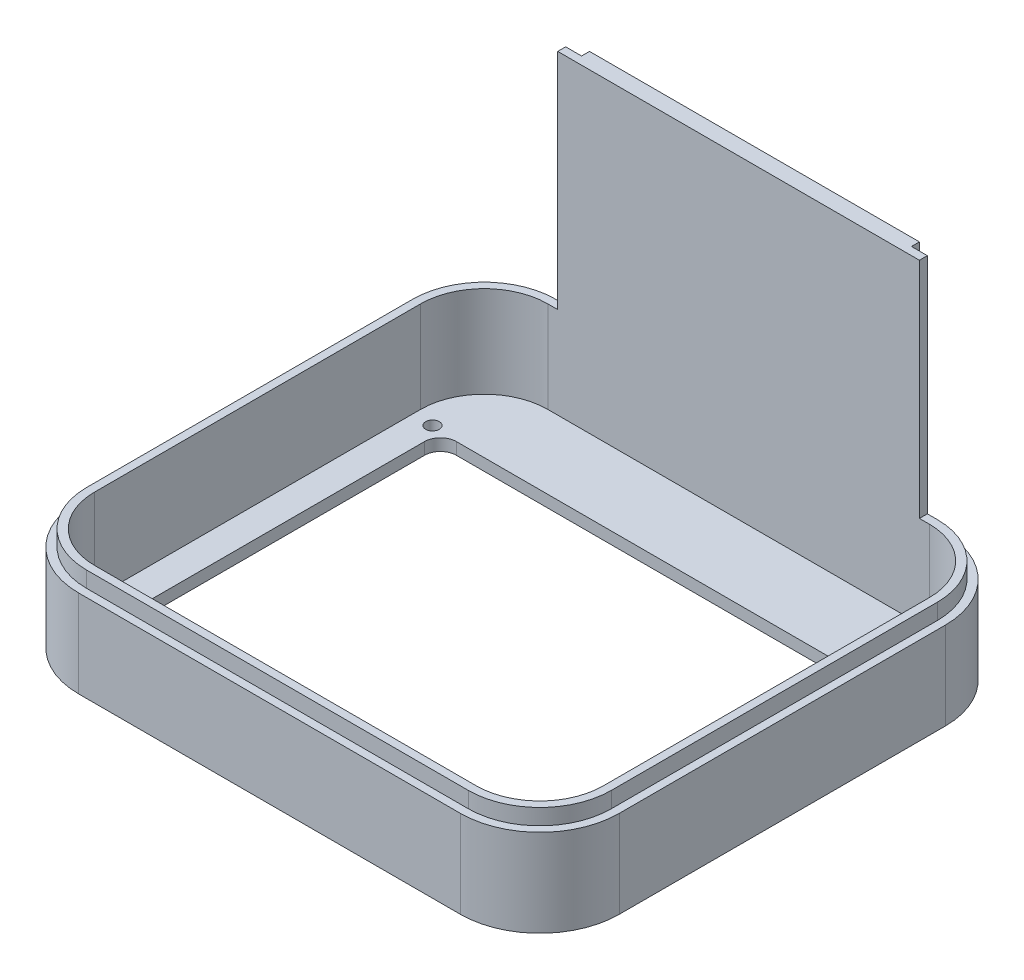
SolidWorks part; units mm, degrees
material "ABS"
ref_plane "Front Plane" through (0, 0, 0) normal (0, 0, 1) x (1, 0, 0)
ref_plane "Top Plane" through (0, 0, 0) normal (0, 1, 0) x (1, 0, 0)
ref_plane "Right Plane" through (0, 0, 0) normal (1, 0, 0) x (0, 0, -1)
sketch "Sketch1" plane through (0, 0, 0) normal (0, 1, 0) x (1, 0, 0)
  line L1 (-68, 61) -> (68, 61)
  line L2 (-68, 61) -> (-68, -61)
  line L3 (-68, -61) -> (68, -61)
  line L4 (68, 61) -> (68, -61)
  line L5 (-68, 61) -> (68, -61) construction
  line L6 (-68, -61) -> (68, 61) construction
  point P0 (0, 0)
  dimension "D1" = 136
  dimension "D2" = 122
extrude "Boss-Extrude1" add sketch "Sketch1" along normal blind 26
fillet "Fillet1" radius 20 4 edges at (-68, 13, 61) (68, 13, 61) (68, 13, -61) (-68, 13, -61)
shell "Shell1" thickness 4
sketch "Sketch2" plane through (0, 3, 0) normal (0, 1, 0) x (1, 0, 0)
  line L1 (-56.5, 38.5) -> (56.5, 38.5)
  line L2 (-56.5, 38.5) -> (-56.5, -38.5)
  line L3 (-56.5, -38.5) -> (56.5, -38.5)
  line L4 (56.5, 38.5) -> (56.5, -38.5)
  line L5 (-56.5, 38.5) -> (56.5, -38.5) construction
  line L6 (-56.5, -38.5) -> (56.5, 38.5) construction
  point P0 (0, 0)
  dimension "D1" = 113
  dimension "D2" = 77
extrude "Cut-Extrude1" cut sketch "Sketch2" against normal up to next
fillet "Fillet2" radius 4 4 edges at (-56.5, 1.5, 38.5) (56.5, 1.5, 38.5) (56.5, 1.5, -38.5) (-56.5, 1.5, -38.5)
hole_wizard "M3 Clearance Hole1" positions "Sketch3" profile "Sketch4" hole size "M3" standard "ANSI Metric" end condition through all
sketch "Sketch3" plane through (0, 3, 0) normal (0, 1, 0) x (1, 0, 0)
  line L0 (0, -14.3) -> (0, 14.3) construction
  line L1 (-14.3, 0) -> (14.3, 0) construction
  line L3 (0, 62.7849) -> (0, -61.8165) construction
  line L5 (-69.9424, 0) -> (69.1851, 0) construction
  point P0 (-59, 39)
  point P17 (59, 39)
  point P20 (59, -39)
  point P21 (-59, -39)
  dimension "D1" = 59
  dimension "D2" = 39
sketch "Sketch4" plane through (-59, 3, -39) normal (1, 0, 0) x (0, 0, 1)
  line L0 (0, 0) -> (0, 3)
  line L1 (0, 3) -> (1.7, 3)
  line L2 (1.7, 3) -> (1.7, 0)
  line L5 (1.7, 0) -> (0, 0)
  line L11 (0, -6.35) -> (0, 107.95) construction
  dimension "Thru Hole Dia." = 3.4
  dimension "Thru Hole Depth" = 3
sketch "Sketch5" plane through (0, 26, 0) normal (0, 1, 0) x (1, 0, 0)
  line L0 (-68, 41) -> (-68, -41) construction
  line L1 (-48, -61) -> (48, -61) construction
  line L2 (68, -41) -> (68, 41) construction
  line L4 (-68, 41) -> (-68, -41)
  line L5 (-48, -61) -> (48, -61)
  line L6 (68, -41) -> (68, 41)
  line L8 (-66, 41) -> (-66, -41)
  line L9 (-48, -59) -> (48, -59)
  line L10 (66, -41) -> (66, 41)
  line L12 (48, 61) -> (-48, 61) construction
  line L13 (48, 59) -> (-48, 59) construction
  line L14 (0, 65.1469) -> (0, 50.8063) construction
  line L15 (0, -46.2) -> (0, 46.2) construction
  line L16 (-48, 61) -> (-41.5, 61)
  line L17 (48, 61) -> (-48, 61) construction
  line L18 (-41.5, 61) -> (-41.5, 59)
  line L19 (-41.5, 59) -> (-48, 59)
  line L20 (41.5, 59) -> (48, 59)
  line L21 (41.5, 61) -> (41.5, 59)
  line L22 (48, 61) -> (41.5, 61)
  arc A0 (-68, -41) -> (-48, -61) centre (-48, -41) ccw construction
  arc A1 (48, -61) -> (68, -41) centre (48, -41) ccw construction
  arc A2 (68, 41) -> (48, 61) centre (48, 41) ccw construction
  arc A3 (-48, 61) -> (-68, 41) centre (-48, 41) ccw construction
  arc A4 (-68, -41) -> (-48, -61) centre (-48, -41) ccw
  arc A5 (48, -61) -> (68, -41) centre (48, -41) ccw
  arc A6 (68, 41) -> (48, 61) centre (48, 41) ccw
  arc A7 (-48, 61) -> (-68, 41) centre (-48, 41) ccw
  arc A8 (-66, -41) -> (-48, -59) centre (-48, -41) ccw
  arc A9 (48, -59) -> (66, -41) centre (48, -41) ccw
  arc A10 (66, 41) -> (48, 59) centre (48, 41) ccw
  arc A11 (-48, 59) -> (-66, 41) centre (-48, 41) ccw
  dimension "D2" = 83
  dimension "D1" = 2
extrude "Cut-Extrude2" cut sketch "Sketch5" against normal blind 4
sketch "Sketch9" plane through (0, 26, 0) normal (0, 1, 0) x (1, 0, 0)
  line L0 (-41.5, 61) -> (-41.5, 59)
  line L1 (-41.5, 59) -> (-45.5, 59)
  line L2 (-48, 59) -> (-41.5, 59) construction
  line L3 (-45.5, 59) -> (-45.5, 57)
  line L4 (48, 57) -> (-48, 57) construction
  line L5 (-45.5, 57) -> (45.5, 57)
  line L6 (-41.5, 61) -> (41.5, 61)
  line L7 (41.5, 61) -> (-41.5, 61) construction
  line L8 (0, 61) -> (0, 57) construction
  line L9 (45.5, 59) -> (45.5, 57)
  line L10 (41.5, 59) -> (45.5, 59)
  line L11 (41.5, 61) -> (41.5, 59)
  dimension "D1" = 4
extrude "Boss-Extrude3" add sketch "Sketch9" along normal blind 56.25
